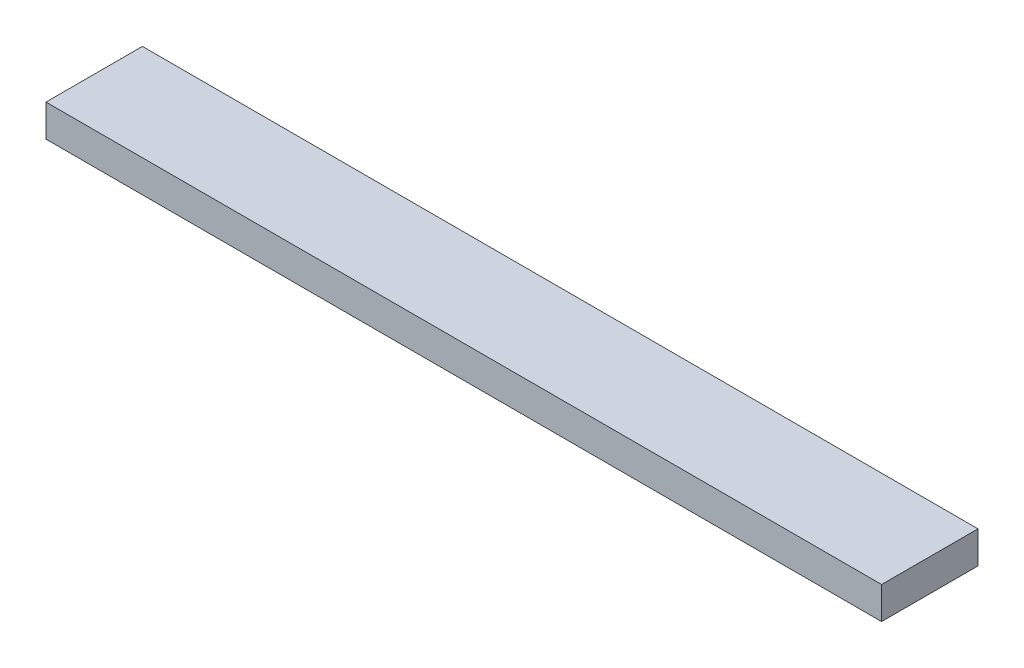
SolidWorks part; units mm, degrees
material "PET"
ref_plane "Front Plane" through (0, 0, 0) normal (0, 0, 1) x (1, 0, 0)
ref_plane "Top Plane" through (0, 0, 0) normal (0, 1, 0) x (1, 0, 0)
ref_plane "Right Plane" through (0, 0, 0) normal (1, 0, 0) x (0, 0, -1)
sketch "CrossSection" plane through (0, 0, 0) normal (1, 0, 0) x (0, 0, -1)
  line L1 (-9.525, 3.175) -> (9.525, 3.175)
  line L2 (-9.525, 3.175) -> (-9.525, -3.175)
  line L3 (-9.525, -3.175) -> (9.525, -3.175)
  line L4 (9.525, 3.175) -> (9.525, -3.175)
  line L5 (-9.525, 3.175) -> (9.525, -3.175) construction
  line L6 (-9.525, -3.175) -> (9.525, 3.175) construction
  point P0 (0, 0)
  dimension "D1" = 6.35
  dimension "D2" = 19.05
extrude "1/4 Inch Thickness" add sketch "CrossSection" along normal mid plane 165.1
sketch "Support Span" plane through (0, 0, 0) normal (0, 1, 0) x (1, 0, 0)
  line L0 (0, 0) -> (50.8, 0) construction
  line L1 (0, 0) -> (-50.8, 0) construction
  line L2 (50.8, 9.525) -> (50.8, -9.525) construction
  line L3 (82.55, 9.525) -> (-82.55, 9.525) construction
  line L4 (82.55, -9.525) -> (-82.55, -9.525) construction
  line L5 (-50.8, 9.525) -> (-50.8, -9.525) construction
  dimension "D1" = 50.8
  dimension "D2" = 101.6
ref_plane "Support 1" through (50.8, 0, 0) normal (1, 0, 0) x (0, 0, -1)
ref_plane "Support 2" through (-50.8, 0, 0) normal (1, 0, 0) x (0, 0, -1)
sketch "Sketch1" [suppressed] plane through (0, 3.175, 0) normal (0, 1, 0) x (1, 0, 0)
  line L0 (-50.8, 9.525) -> (-50.8, -9.525) construction
  line L1 (50.8, 9.525) -> (50.8, -9.525) construction
  line L2 (-50.8, 9.525) -> (-50.8, -9.525) construction
  line L3 (50.8, 9.525) -> (50.8, -9.525) construction
equation "\"D1@Support Span\" = \"D1@CrossSection\" * 8"
equation "\"D2@Support Span\" = \"D1@CrossSection\" * 16"
